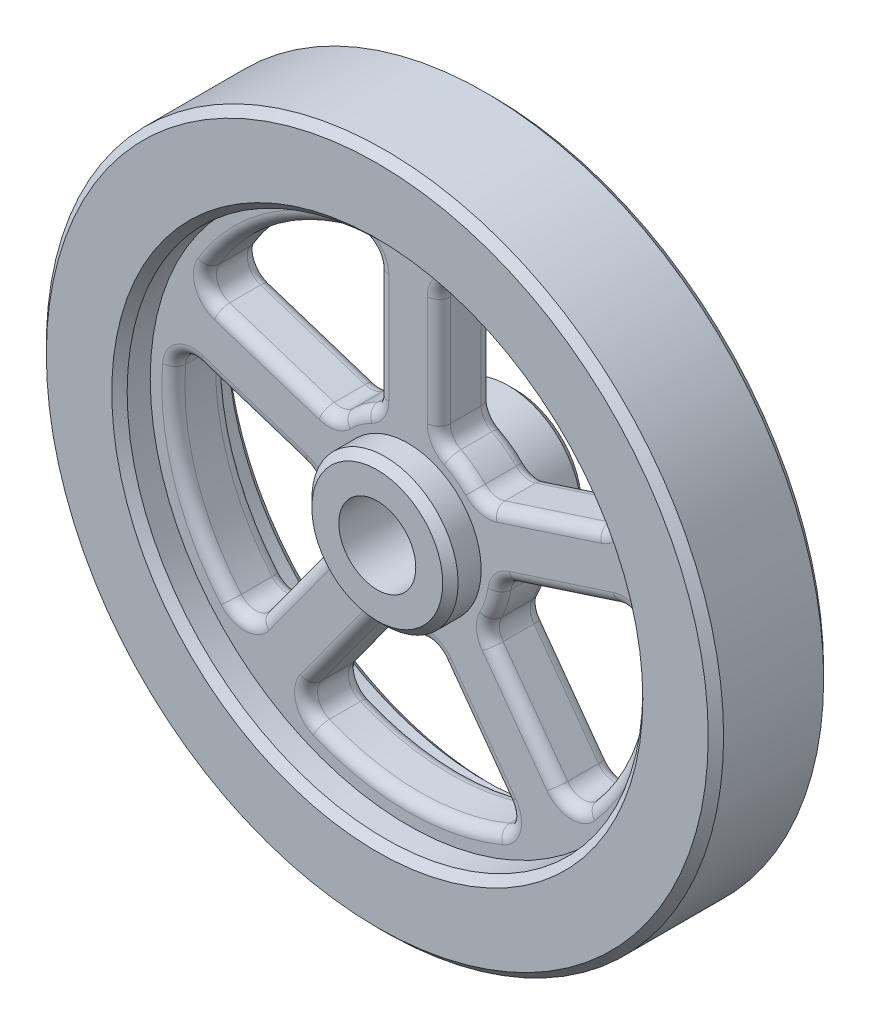
SolidWorks part; units mm, degrees
material "1345 Alloy"
ref_plane "Front Plane" through (0, 0, 0) normal (0, 0, 1) x (1, 0, 0)
ref_plane "Top Plane" through (0, 0, 0) normal (0, 1, 0) x (1, 0, 0)
ref_plane "Right Plane" through (0, 0, 0) normal (1, 0, 0) x (0, 0, -1)
sketch "Sketch1" plane through (0, 0, 0) normal (0, 0, 1) x (1, 0, 0)
  circle A0 centre (0, 0) radius 44
  circle A1 centre (0, 0) radius 33.5
  dimension "D1" = 88
  dimension "D2" = 67
extrude "Boss-Extrude1" add sketch "Sketch1" along normal mid plane 15
sketch "Sketch2" plane through (0, 0, 0) normal (0, 0, 1) x (1, 0, 0)
  circle A2 centre (0, 0) radius 33.5
  circle A3 centre (0, 0) radius 33.5
  dimension "D1" = 0
extrude "Boss-Extrude2" add sketch "Sketch2" along normal mid plane 7
sketch "Sketch3" plane through (0, 0, 3.5) normal (0, 0, 1) x (1, 0, 0)
  circle A0 centre (0, 0) radius 5
  circle A1 centre (0, 0) radius 33.5 construction
extrude "Cut-Extrude1" cut sketch "Sketch3" against normal through all
chamfer "Chamfer1" distance 1 angle 45 4 edges at (33.5, 0, -7.5) (44, 0, -7.5) (33.5, 0, 7.5) (44, 0, 7.5)
sketch "Sketch5" plane through (0, 0, 3.5) normal (0, 0, 1) x (1, 0, 0)
  line L0 (0, 0) -> (0, 40.4369) construction
  line L1 (0, 0) -> (54.9873, 17.8665) construction
  line L4 (4, 11.3137) -> (4, 30.2366)
  line L5 (9.5239, 7.3004) -> (27.5206, 13.1478)
  arc A0 (27.5206, 13.1478) -> (4, 30.2366) centre (0, 0) ccw
  arc A1 (9.5239, 7.3004) -> (4, 11.3137) centre (0, 0) ccw
  point P3 (4, 0)
  point P5 (4, 40.4369)
  point P6 (-1.2361, 3.8042)
  point P7 (53.7512, 21.6707)
  dimension "D1" = 72
extrude "Cut-Extrude2" cut sketch "Sketch5" against normal through all
pattern_circular "CirPattern1" count 5 every 72 about axis through (0, 0, 0) along (0, 0, 1) of "Cut-Extrude2"
sketch "Sketch6" plane through (0, 0, 7.5) normal (0, 0, 1) x (1, 0, 0)
  circle A0 centre (0, 0) radius 9.5
extrude "Boss-Extrude3" add sketch "Sketch6" against normal blind 18
sketch "Sketch7" plane through (0, 0, 7.5) normal (0, 0, 1) x (1, 0, 0)
  circle A0 centre (0, 0) radius 5
extrude "Cut-Extrude3" cut sketch "Sketch7" against normal through all
sketch "Sketch8" plane through (0, 0, 0) normal (0, 1, 0) x (1, 0, 0)
  line L0 (5, 10.5) -> (-5, 10.5) construction
  circle A0 centre (0, 5) radius 2
  dimension "D1" = 4
  dimension "D2" = 5.5
extrude "Cut-Extrude4" [suppressed] cut sketch "Sketch8" against normal through all
chamfer "Chamfer2" distance 1 angle 45 2 edges at (9.5, 0, -10.5) (9.5, 0, 7.5)
fillet "Fillet1" radius 2.5 20 edges at (-27.5206, 13.1478, 0) (-4, 30.2366, 0) (-29.9928, 5.5394, 0) (-4, 11.3137, 0) (-9.5239, 7.3004, 0) (-21.0087, -22.1108, 0) (-9.8861, -6.8018, 0) (-11.996, -0.3081, 0) (-3.414, -11.5041, 0) (3.414, -11.5041, 0) (14.5365, -26.813, 0) (-14.5365, -26.813, 0) (9.8861, -6.8018, 0) (21.0087, -22.1108, 0) (29.9928, 5.5394, 0) (11.996, -0.3081, 0) (9.5239, 7.3004, 0) (4, 11.3137, 0) (4, 30.2366, 0) (27.5206, 13.1478, 0)
fillet "Fillet2" radius 1.5 16 edges at (9.7271, 7.7581, 3.5) (7.0534, 9.7082, 3.5) (4.3726, 11.6484, 3.5) (4, 20.0983, 3.5) (4.951, 29.1973, 3.5) (17.9275, 24.675, 3.5) (26.2384, 13.7311, 3.5) (4.3726, 11.6484, -3.5) (4, 20.0983, -3.5) (4.951, 29.1973, -3.5) (17.9275, 24.675, -3.5) (26.2384, 13.7311, -3.5) (9.7271, 7.7581, -3.5) (17.8785, 10.0149, 3.5) (17.8785, 10.0149, -3.5) (7.0534, 9.7082, -3.5)
fillet "Fillet3" radius 1.5 64 edges at (21.1672, -20.7111, 3.5) (15.0495, -13.9087, 3.5) (10.3843, -6.8536, 3.5) (11.4127, -3.7082, 3.5) (12.4295, -0.559, 3.5) (20.3507, 2.4065, 3.5) (29.2983, 4.3138, 3.5) (21.1672, -20.7111, -3.5) (15.0495, -13.9087, -3.5) (10.3843, -6.8536, -3.5) (11.4127, -3.7082, -3.5) (12.4295, -0.559, -3.5) (20.3507, 2.4065, -3.5) (29.2983, 4.3138, -3.5) (-13.1564, -26.5312, -3.5) (-8.5774, -18.611, -3.5) (-3.3093, -11.9939, -3.5) (0, -12, -3.5) (3.3093, -11.9939, -3.5) (8.5774, -18.611, -3.5) (13.1564, -26.5312, -3.5) (-13.1564, -26.5312, 3.5) (-8.5774, -18.611, 3.5) (-3.3093, -11.9939, 3.5) (0, -12, 3.5) (3.3093, -11.9939, 3.5) (8.5774, -18.611, 3.5) (13.1564, -26.5312, 3.5) (-21.1672, -20.7111, 3.5) (-29.0072, -9.425, 3.5) (-29.2983, 4.3138, 3.5) (-20.3507, 2.4065, 3.5) (-12.4295, -0.559, 3.5) (-11.4127, -3.7082, 3.5) (-10.3843, -6.8536, 3.5) (-21.1672, -20.7111, -3.5) (-29.0072, -9.425, -3.5) (-29.2983, 4.3138, -3.5) (-20.3507, 2.4065, -3.5) (-12.4295, -0.559, -3.5) (-11.4127, -3.7082, -3.5) (-10.3843, -6.8536, -3.5) (-4.3726, 11.6484, 3.5) (-7.0534, 9.7082, 3.5) (-9.7271, 7.7581, 3.5) (-17.8785, 10.0149, 3.5) (-26.2384, 13.7311, 3.5) (-17.9275, 24.675, 3.5) (-4.951, 29.1973, 3.5) (-26.2384, 13.7311, -3.5) (-17.9275, 24.675, -3.5) (-4.951, 29.1973, -3.5) (-4.3726, 11.6484, -3.5) (-7.0534, 9.7082, -3.5) (-9.7271, 7.7581, -3.5) (29.0072, -9.425, 3.5) (29.0072, -9.425, -3.5) (0, -30.5, -3.5) (0, -30.5, 3.5) (-15.0495, -13.9087, 3.5) (-15.0495, -13.9087, -3.5) (-4, 20.0983, -3.5) (-4, 20.0983, 3.5) (-17.8785, 10.0149, -3.5)
